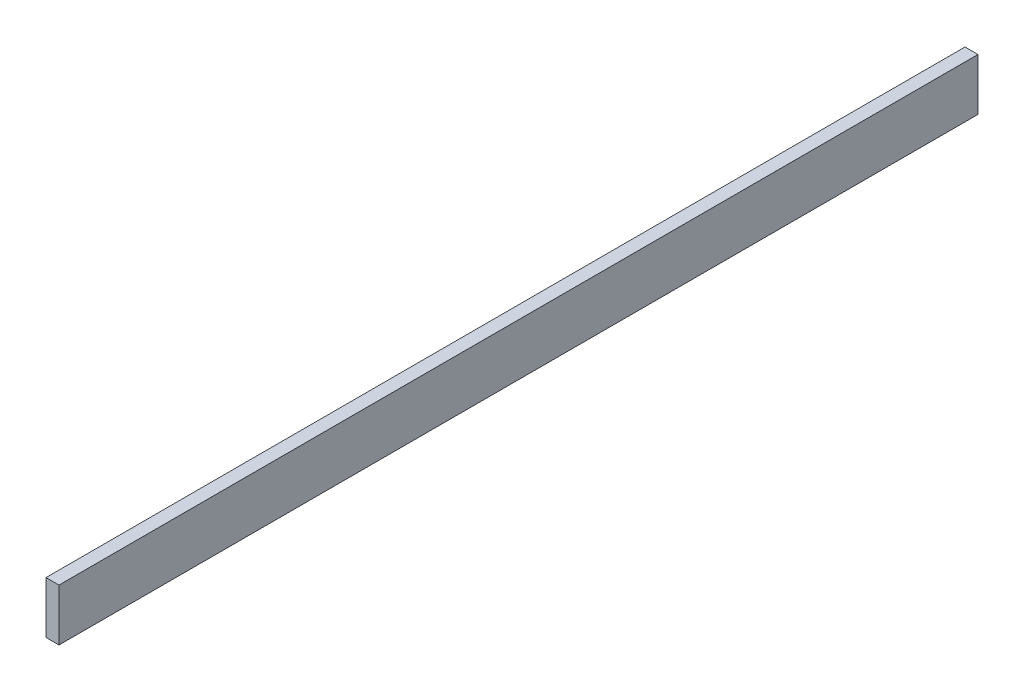
SolidWorks part; units mm, degrees
ref_plane "Front Plane" through (0, 0, 0) normal (0, 0, 1) x (1, 0, 0)
ref_plane "Top Plane" through (0, 0, 0) normal (0, 1, 0) x (1, 0, 0)
ref_plane "Right Plane" through (0, 0, 0) normal (1, 0, 0) x (0, 0, -1)
sketch "Sketch1" plane through (0, 0, 0) normal (0, 0, 1) x (1, 0, 0)
  line L1 (0, 0) -> (3.175, 0)
  line L2 (0, 0) -> (0, 12.7)
  line L3 (0, 12.7) -> (3.175, 12.7)
  line L4 (3.175, 0) -> (3.175, 12.7)
  dimension "D1" = 12.7
  dimension "D2" = 3.175
extrude "Boss-Extrude1" add sketch "Sketch1" along normal blind 224.79
